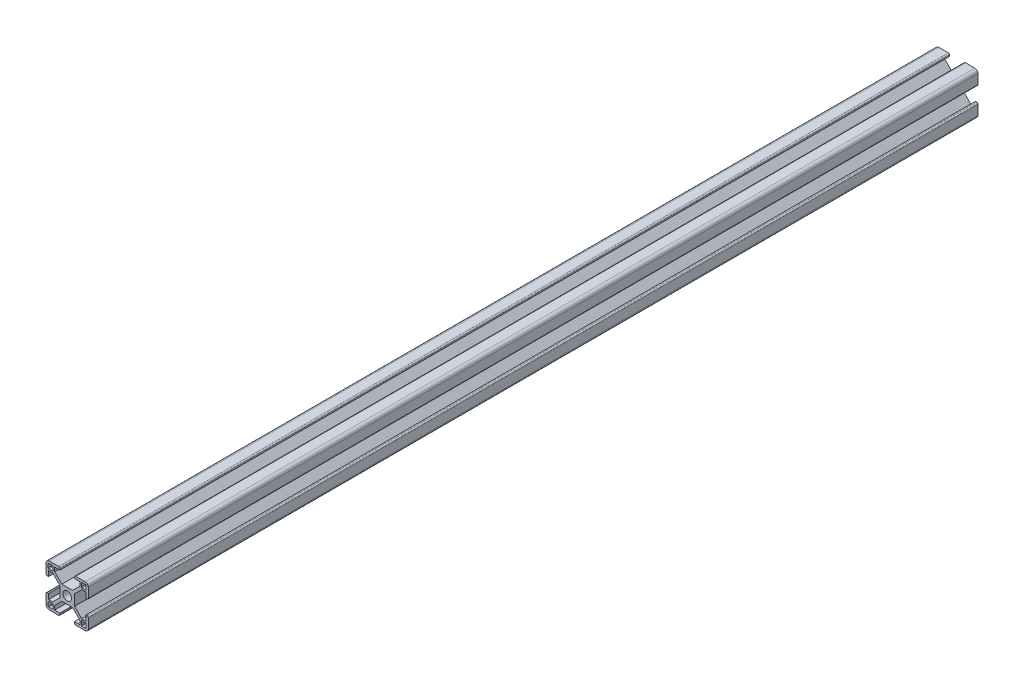
SolidWorks part; units mm, degrees
ref_plane "Alzado" through (0, 0, 0) normal (0, 0, 1) x (1, 0, 0)
ref_plane "Planta" through (0, 0, 0) normal (0, 1, 0) x (1, 0, 0)
ref_plane "Vista lateral" through (0, 0, 0) normal (1, 0, 0) x (0, 0, -1)
sketch "Croquis1" plane through (0, 0, 0) normal (0, 0, 1) x (1, 0, 0)
  line L0 (-5.8, 0) -> (5.8, 0) construction
  line L1 (5.8, -4.24) -> (5.8, 4.24)
  line L2 (5.8, 4.24) -> (11.47, 9.91)
  line L3 (11.47, 9.91) -> (14.66, 9.91)
  line L4 (14.66, 9.91) -> (14.66, 5.73)
  line L5 (14.66, 5.73) -> (15.66, 5.73)
  line L6 (16.66, 6.73) -> (16.66, 14.16)
  line L7 (0, 0) -> (16.66, 16.66) construction
  line L8 (5.73, 14.66) -> (5.73, 15.66)
  line L9 (6.73, 16.66) -> (14.16, 16.66)
  line L10 (9.91, 14.66) -> (5.73, 14.66)
  line L11 (9.91, 11.47) -> (9.91, 14.66)
  line L12 (4.24, 5.8) -> (9.91, 11.47)
  line L13 (-4.24, 5.8) -> (4.24, 5.8)
  line L14 (0, 5.8) -> (0, -5.8) construction
  line L15 (11.6515, 14.9015) -> (14.4015, 14.9015)
  line L16 (11.1515, 14.4015) -> (11.1515, 11.6515)
  line L17 (11.6515, 11.1515) -> (14.4015, 11.1515)
  line L18 (14.9015, 14.4015) -> (14.9015, 11.6515)
  line L19 (11.1515, 14.9015) -> (14.9015, 11.1515) construction
  line L20 (11.1515, 11.1515) -> (14.9015, 14.9015) construction
  line L21 (-11.1515, 11.1515) -> (-14.9015, 14.9015) construction
  line L22 (-11.1515, 14.9015) -> (-14.9015, 11.1515) construction
  line L23 (0, 0) -> (-16.66, 16.66) construction
  line L24 (-14.9015, 14.4015) -> (-14.9015, 11.6515)
  line L25 (-11.6515, 11.1515) -> (-14.4015, 11.1515)
  line L26 (-11.1515, 14.4015) -> (-11.1515, 11.6515)
  line L27 (-11.6515, 14.9015) -> (-14.4015, 14.9015)
  line L28 (-4.24, 5.8) -> (-9.91, 11.47)
  line L29 (-9.91, 11.47) -> (-9.91, 14.66)
  line L30 (-9.91, 14.66) -> (-5.73, 14.66)
  line L31 (-6.73, 16.66) -> (-14.16, 16.66)
  line L32 (-5.73, 14.66) -> (-5.73, 15.66)
  line L33 (-16.66, 6.73) -> (-16.66, 14.16)
  line L34 (-14.66, 5.73) -> (-15.66, 5.73)
  line L35 (-14.66, 9.91) -> (-14.66, 5.73)
  line L36 (-11.47, 9.91) -> (-14.66, 9.91)
  line L37 (-5.8, 4.24) -> (-11.47, 9.91)
  line L38 (-5.8, -4.24) -> (-5.8, 4.24)
  line L39 (0, 0) -> (-16.66, -16.66) construction
  line L40 (-11.1515, -14.9015) -> (-14.9015, -11.1515) construction
  line L41 (-11.1515, -11.1515) -> (-14.9015, -14.9015) construction
  line L42 (11.1515, -11.1515) -> (14.9015, -14.9015) construction
  line L43 (11.1515, -14.9015) -> (14.9015, -11.1515) construction
  line L44 (0, 0) -> (16.66, -16.66) construction
  line L45 (-5.8, -4.24) -> (-11.47, -9.91)
  line L46 (-11.47, -9.91) -> (-14.66, -9.91)
  line L47 (-14.66, -9.91) -> (-14.66, -5.73)
  line L48 (-14.66, -5.73) -> (-15.66, -5.73)
  line L49 (-16.66, -6.73) -> (-16.66, -14.16)
  line L50 (-5.73, -14.66) -> (-5.73, -15.66)
  line L51 (-6.73, -16.66) -> (-14.16, -16.66)
  line L52 (-9.91, -14.66) -> (-5.73, -14.66)
  line L53 (-9.91, -11.47) -> (-9.91, -14.66)
  line L54 (-4.24, -5.8) -> (-9.91, -11.47)
  line L55 (-11.6515, -14.9015) -> (-14.4015, -14.9015)
  line L56 (-11.1515, -14.4015) -> (-11.1515, -11.6515)
  line L57 (-11.6515, -11.1515) -> (-14.4015, -11.1515)
  line L58 (-14.9015, -14.4015) -> (-14.9015, -11.6515)
  line L59 (14.9015, -14.4015) -> (14.9015, -11.6515)
  line L60 (11.6515, -11.1515) -> (14.4015, -11.1515)
  line L61 (11.1515, -14.4015) -> (11.1515, -11.6515)
  line L62 (11.6515, -14.9015) -> (14.4015, -14.9015)
  line L63 (-4.24, -5.8) -> (4.24, -5.8)
  line L64 (4.24, -5.8) -> (9.91, -11.47)
  line L65 (9.91, -11.47) -> (9.91, -14.66)
  line L66 (9.91, -14.66) -> (5.73, -14.66)
  line L67 (6.73, -16.66) -> (14.16, -16.66)
  line L68 (5.73, -14.66) -> (5.73, -15.66)
  line L69 (16.66, -6.73) -> (16.66, -14.16)
  line L70 (14.66, -5.73) -> (15.66, -5.73)
  line L71 (14.66, -9.91) -> (14.66, -5.73)
  line L72 (11.47, -9.91) -> (14.66, -9.91)
  line L73 (5.8, -4.24) -> (11.47, -9.91)
  arc A0 (15.66, 5.73) -> (16.66, 6.73) centre (15.66, 6.73) ccw
  arc A1 (16.66, 14.16) -> (14.16, 16.66) centre (14.16, 14.16) ccw
  arc A2 (5.73, 15.66) -> (6.73, 16.66) centre (6.73, 15.66) cw
  arc A3 (11.1515, 11.6515) -> (11.6515, 11.1515) centre (11.6515, 11.6515) ccw
  arc A4 (14.4015, 11.1515) -> (14.9015, 11.6515) centre (14.4015, 11.6515) ccw
  arc A5 (14.4015, 14.9015) -> (14.9015, 14.4015) centre (14.4015, 14.4015) cw
  arc A6 (11.6515, 14.9015) -> (11.1515, 14.4015) centre (11.6515, 14.4015) ccw
  arc A7 (-11.6515, 14.9015) -> (-11.1515, 14.4015) centre (-11.6515, 14.4015) cw
  arc A8 (-14.4015, 14.9015) -> (-14.9015, 14.4015) centre (-14.4015, 14.4015) ccw
  arc A9 (-14.4015, 11.1515) -> (-14.9015, 11.6515) centre (-14.4015, 11.6515) cw
  arc A10 (-11.1515, 11.6515) -> (-11.6515, 11.1515) centre (-11.6515, 11.6515) cw
  arc A11 (-5.73, 15.66) -> (-6.73, 16.66) centre (-6.73, 15.66) ccw
  arc A12 (-16.66, 14.16) -> (-14.16, 16.66) centre (-14.16, 14.16) cw
  arc A13 (-15.66, 5.73) -> (-16.66, 6.73) centre (-15.66, 6.73) cw
  arc A14 (-15.66, -5.73) -> (-16.66, -6.73) centre (-15.66, -6.73) ccw
  arc A15 (-16.66, -14.16) -> (-14.16, -16.66) centre (-14.16, -14.16) ccw
  arc A16 (-5.73, -15.66) -> (-6.73, -16.66) centre (-6.73, -15.66) cw
  arc A17 (-11.1515, -11.6515) -> (-11.6515, -11.1515) centre (-11.6515, -11.6515) ccw
  arc A18 (-14.4015, -11.1515) -> (-14.9015, -11.6515) centre (-14.4015, -11.6515) ccw
  arc A19 (-14.4015, -14.9015) -> (-14.9015, -14.4015) centre (-14.4015, -14.4015) cw
  arc A20 (-11.6515, -14.9015) -> (-11.1515, -14.4015) centre (-11.6515, -14.4015) ccw
  arc A21 (11.6515, -14.9015) -> (11.1515, -14.4015) centre (11.6515, -14.4015) cw
  arc A22 (14.4015, -14.9015) -> (14.9015, -14.4015) centre (14.4015, -14.4015) ccw
  arc A23 (14.4015, -11.1515) -> (14.9015, -11.6515) centre (14.4015, -11.6515) cw
  arc A24 (11.1515, -11.6515) -> (11.6515, -11.1515) centre (11.6515, -11.6515) cw
  arc A25 (5.73, -15.66) -> (6.73, -16.66) centre (6.73, -15.66) ccw
  arc A26 (16.66, -14.16) -> (14.16, -16.66) centre (14.16, -14.16) cw
  arc A27 (15.66, -5.73) -> (16.66, -6.73) centre (15.66, -6.73) cw
  circle A28 centre (0, 0) radius 3.4
  point P17 (16.66, 5.73)
  point P23 (5.73, 16.66)
  point P24 (13.0265, 13.0265)
  point P76 (-13.0265, 13.0265)
  point P77 (-5.73, 16.66)
  point P78 (-16.66, 5.73)
  point P148 (-16.66, -5.73)
  point P149 (-5.73, -16.66)
  point P150 (-13.0265, -13.0265)
  point P151 (13.0265, -13.0265)
  point P152 (5.73, -16.66)
  point P153 (16.66, -5.73)
  dimension "D9" = 1
  dimension "D10" = 2.5
  dimension "D11" = 1
  dimension "D14" = 0.5
  dimension "D15" = 6.8
  dimension "D2" = 4.24
  dimension "D3" = 135
  dimension "D4" = 5.67
  dimension "D5" = 3.19
  dimension "D6" = 4.18
  dimension "D7" = 10.93
  dimension "D8" = 2
  dimension "D12" = 3.75
  dimension "D13" = 3.75
extrude "Saliente-Extruir3" add sketch "Croquis1" along normal blind 700
